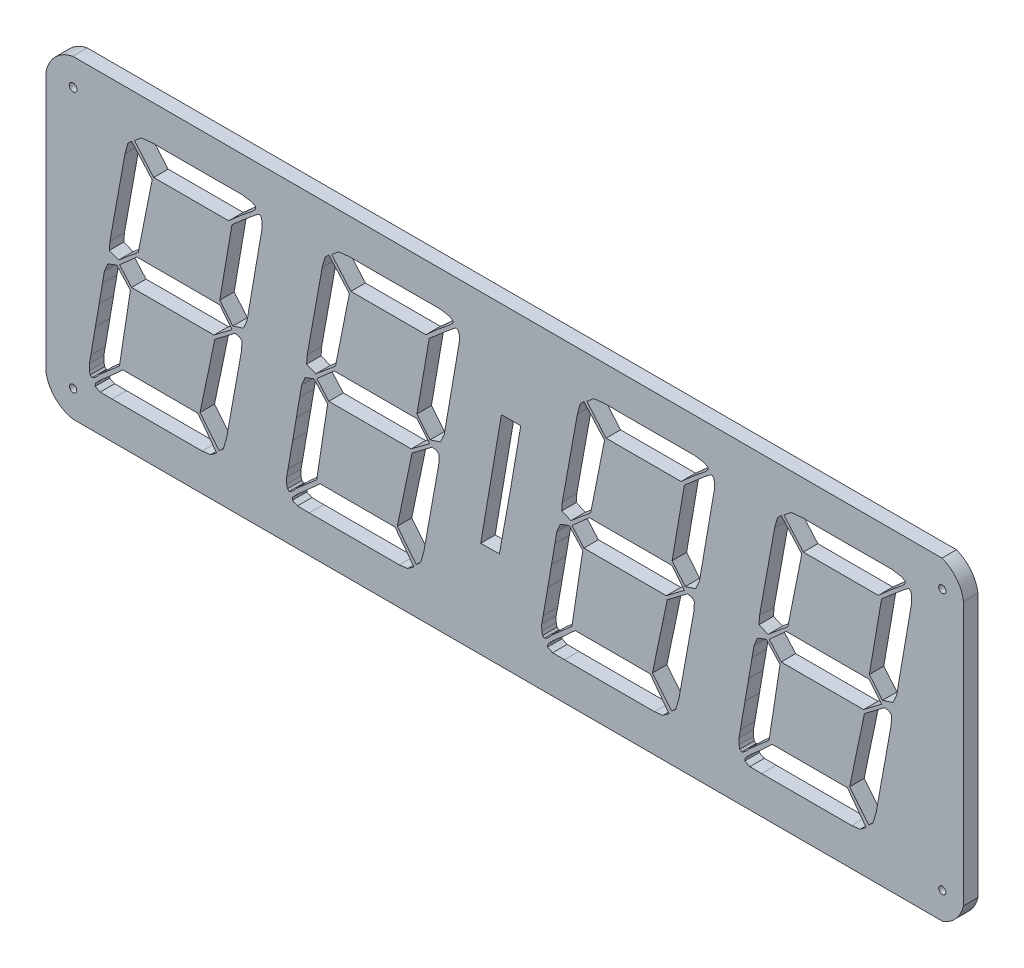
SolidWorks part; units mm, degrees
ref_plane "Alzado" through (0, 0, 0) normal (0, 0, 1) x (1, 0, 0)
ref_plane "Planta" through (0, 0, 0) normal (0, 1, 0) x (1, 0, 0)
ref_plane "Vista lateral" through (0, 0, 0) normal (1, 0, 0) x (0, 0, -1)
sketch "Model" plane through (0, 0, 0) normal (0, 0, 1) x (1, 0, 0)
  line L0 (-140.6225, 55.7522) -> (-140.6299, -52.2478)
  line L1 (-129.5522, 66.8002) -> (230.4478, 66.8126)
  line L2 (239.3651, 55.7522) -> (239.368, -53.5141)
  line L3 (230.8631, -63.3329) -> (-129.5522, -63.3205)
  line L4 (-64.9575, 40.0838) -> (-96.0301, 40.0838)
  line L5 (-96.0301, 40.0838) -> (-103.9988, 49.3198)
  line L6 (-110.1562, 1.7368) -> (-102.93, 8.0807)
  line L7 (-102.93, 8.0807) -> (-68.6104, 8.0807)
  line L8 (-68.6104, 8.0807) -> (-63.6119, 1.7368)
  line L9 (-63.6119, 1.7368) -> (-71.0723, -3.9362)
  line L10 (-71.0723, -3.9362) -> (-105.2054, -3.9362)
  line L11 (-105.2054, -3.9362) -> (-110.1562, 1.7368)
  line L12 (-108.8288, -35.3192) -> (-77.7561, -35.3192)
  line L13 (-77.7561, -35.3192) -> (-69.9507, -45.704)
  line L14 (-55.7324, 46.1598) -> (-63.6119, 39.3989)
  line L15 (-63.6119, 39.3989) -> (-68.6828, 9.7484)
  line L16 (-68.6828, 9.7484) -> (-63.2554, 3.1978)
  line L17 (-105.1896, 48.562) -> (-96.6695, 38.9507)
  line L18 (-96.6695, 38.9507) -> (-102.4115, 10.0574)
  line L19 (-102.4115, 10.0574) -> (-110.5903, 3.1978)
  line L20 (-114.1475, 8.141) -> (-107.9276, 42.67)
  line L21 (-118.6586, -41.9453) -> (-110.2023, -34.6026)
  line L22 (-110.2023, -34.6026) -> (-105.6821, -5.1361)
  line L23 (-105.6821, -5.1361) -> (-111.3311, 1.0276)
  line L24 (-68.9232, -44.3791) -> (-76.8319, -34.6002)
  line L25 (-76.8319, -34.6002) -> (-70.708, -5.2612)
  line L26 (-70.708, -5.2612) -> (-62.3439, 1.0154)
  line L27 (-59.6661, -3.9289) -> (-65.8858, -38.4574)
  line L28 (16.7253, 40.0838) -> (-14.3473, 40.0838)
  line L29 (-14.3473, 40.0838) -> (-22.316, 49.3198)
  line L30 (-28.4733, 1.7368) -> (-21.2471, 8.0807)
  line L31 (-21.2471, 8.0807) -> (13.0724, 8.0807)
  line L32 (13.0724, 8.0807) -> (18.1947, 1.7368)
  line L33 (18.1947, 1.7368) -> (10.6105, -3.9362)
  line L34 (10.6105, -3.9362) -> (-23.5226, -3.9362)
  line L35 (-23.5226, -3.9362) -> (-28.4733, 1.7368)
  line L36 (-27.1459, -35.3192) -> (3.9267, -35.3192)
  line L37 (3.9267, -35.3192) -> (11.7321, -45.704)
  line L38 (25.9504, 46.1916) -> (18.071, 39.4307)
  line L39 (18.071, 39.4307) -> (13, 9.7801)
  line L40 (13, 9.7801) -> (18.4274, 3.2296)
  line L41 (-23.5068, 48.5938) -> (-14.9867, 38.9825)
  line L42 (-14.9867, 38.9825) -> (-20.7287, 10.0892)
  line L43 (-20.7287, 10.0892) -> (-28.9075, 3.2296)
  line L44 (-32.4647, 8.1728) -> (-26.2448, 42.7018)
  line L45 (-36.9758, -41.9135) -> (-28.5195, -34.5709)
  line L46 (-28.5195, -34.5709) -> (-23.9993, -5.1043)
  line L47 (-23.9993, -5.1043) -> (-29.6483, 1.0594)
  line L48 (12.7596, -44.3473) -> (4.8509, -34.5684)
  line L49 (4.8509, -34.5684) -> (10.9749, -5.2294)
  line L50 (10.9749, -5.2294) -> (19.3389, 1.0472)
  line L51 (22.0168, -3.8971) -> (15.797, -38.4256)
  line L52 (122.4056, 40.26) -> (91.3329, 40.26)
  line L53 (91.3329, 40.26) -> (83.3642, 49.496)
  line L54 (77.2069, 1.913) -> (84.3607, 8.2568)
  line L55 (84.3607, 8.2568) -> (118.6802, 8.2568)
  line L56 (118.6802, 8.2568) -> (123.7512, 1.913)
  line L57 (123.7512, 1.913) -> (116.2907, -3.7601)
  line L58 (116.2907, -3.7601) -> (82.1576, -3.7601)
  line L59 (82.1576, -3.7601) -> (77.2069, 1.913)
  line L60 (78.5343, -35.143) -> (109.6069, -35.143)
  line L61 (109.6069, -35.143) -> (117.4122, -45.5279)
  line L62 (131.6306, 46.3995) -> (123.7512, 39.6386)
  line L63 (123.7512, 39.6386) -> (118.6802, 9.9881)
  line L64 (118.6802, 9.9881) -> (124.1076, 3.4375)
  line L65 (82.1734, 48.8017) -> (90.6935, 39.1904)
  line L66 (90.6935, 39.1904) -> (84.9515, 10.2971)
  line L67 (84.9515, 10.2971) -> (76.7727, 3.4375)
  line L68 (73.2155, 8.3807) -> (79.4354, 42.9097)
  line L69 (68.7044, -41.7056) -> (77.1607, -34.3629)
  line L70 (77.1607, -34.3629) -> (81.6809, -4.8964)
  line L71 (81.6809, -4.8964) -> (76.0319, 1.2673)
  line L72 (118.4398, -44.1394) -> (110.5311, -34.3605)
  line L73 (110.5311, -34.3605) -> (116.6551, -5.0215)
  line L74 (116.6551, -5.0215) -> (125.0191, 1.2552)
  line L75 (127.697, -3.6892) -> (121.4772, -38.2177)
  line L76 (204.0884, 40.26) -> (173.0157, 40.26)
  line L77 (173.0157, 40.26) -> (165.047, 49.496)
  line L78 (158.8897, 1.913) -> (165.9593, 8.2568)
  line L79 (165.9593, 8.2568) -> (200.2788, 8.2568)
  line L80 (200.2788, 8.2568) -> (205.434, 1.913)
  line L81 (205.434, 1.913) -> (197.9736, -3.7601)
  line L82 (197.9736, -3.7601) -> (163.8405, -3.7601)
  line L83 (163.8405, -3.7601) -> (158.8897, 1.913)
  line L84 (160.2171, -35.143) -> (191.2898, -35.143)
  line L85 (191.2898, -35.143) -> (199.0951, -45.5279)
  line L86 (213.3134, 46.4313) -> (205.434, 39.6704)
  line L87 (205.434, 39.6704) -> (200.363, 10.0198)
  line L88 (200.363, 10.0198) -> (205.7903, 3.4693)
  line L89 (163.8562, 48.8335) -> (172.3763, 39.2222)
  line L90 (172.3763, 39.2222) -> (166.6343, 10.3289)
  line L91 (166.6343, 10.3289) -> (158.4554, 3.4693)
  line L92 (154.8984, 8.4125) -> (161.1182, 42.9415)
  line L93 (150.3872, -41.6738) -> (158.8435, -34.3311)
  line L94 (158.8435, -34.3311) -> (163.3638, -4.8646)
  line L95 (163.3638, -4.8646) -> (157.7147, 1.2991)
  line L96 (200.1227, -44.1076) -> (192.214, -34.3287)
  line L97 (192.214, -34.3287) -> (198.3379, -4.9897)
  line L98 (198.3379, -4.9897) -> (206.7019, 1.2869)
  line L99 (209.3798, -3.6574) -> (203.1599, -38.1859)
  line L100 (-103.9988, 49.3198) -> (-101.137, 51.7291)
  line L101 (-101.137, 51.7291) -> (-96.392, 52.2351)
  line L102 (-96.392, 52.2351) -> (-90.8081, 52.1862)
  line L103 (-90.8081, 52.1862) -> (-81.4945, 52.1759)
  line L104 (-81.4945, 52.1759) -> (-71.5603, 52.1951)
  line L105 (-71.5603, 52.1951) -> (-59.3236, 52.2382)
  line L106 (-59.3236, 52.2382) -> (-55.3145, 51.5899)
  line L107 (-55.3145, 51.5899) -> (-53.8742, 50.7516)
  line L108 (-53.8742, 50.7516) -> (-53.7847, 49.9239)
  line L109 (-53.7847, 49.9239) -> (-55.0086, 48.562)
  line L110 (-55.0086, 48.562) -> (-60.0916, 44.4166)
  line L111 (-60.0916, 44.4166) -> (-64.9575, 40.0838)
  line L112 (-69.9507, -45.704) -> (-72.4976, -47.5521)
  line L113 (-72.4976, -47.5521) -> (-75.986, -47.9957)
  line L114 (-75.986, -47.9957) -> (-113.2949, -47.9957)
  line L115 (-113.2949, -47.9957) -> (-118.1689, -47.9461)
  line L116 (-118.1689, -47.9461) -> (-120.2715, -46.9653)
  line L117 (-120.2715, -46.9653) -> (-120.1336, -45.794)
  line L118 (-120.1336, -45.794) -> (-118.0338, -43.5885)
  line L119 (-118.0338, -43.5885) -> (-114.0258, -40.0909)
  line L120 (-114.0258, -40.0909) -> (-108.8288, -35.3192)
  line L121 (-52.2008, 48.7284) -> (-52.3111, 48.7191)
  line L122 (-52.3111, 48.7191) -> (-52.434, 48.6747)
  line L123 (-52.434, 48.6747) -> (-52.7329, 48.5137)
  line L124 (-52.7329, 48.5137) -> (-53.5199, 47.9663)
  line L125 (-53.5199, 47.9663) -> (-55.7324, 46.1598)
  line L126 (-63.2554, 3.1978) -> (-58.9197, 4.5919)
  line L127 (-58.9197, 4.5919) -> (-57.3622, 8.0171)
  line L128 (-57.3622, 8.0171) -> (-56.5792, 12.6326)
  line L129 (-56.5792, 12.6326) -> (-55.1781, 20.8191)
  line L130 (-55.1781, 20.8191) -> (-53.6437, 29.7566)
  line L131 (-53.6437, 29.7566) -> (-51.7277, 40.8987)
  line L132 (-51.7277, 40.8987) -> (-51.1301, 44.252)
  line L133 (-51.1301, 44.252) -> (-51.1454, 46.7087)
  line L134 (-51.1454, 46.7087) -> (-51.4988, 48.1027)
  line L135 (-51.4988, 48.1027) -> (-52.2008, 48.7284)
  line L136 (-107.9276, 42.67) -> (-106.7219, 47.0167)
  line L137 (-106.7219, 47.0167) -> (-105.1896, 48.562)
  line L138 (-110.5903, 3.1978) -> (-114.3946, 4.748)
  line L139 (-114.3946, 4.748) -> (-114.1475, 8.141)
  line L140 (-111.3311, 1.0276) -> (-115.0422, -0.3762)
  line L141 (-115.0422, -0.3762) -> (-116.4501, -3.8038)
  line L142 (-116.4501, -3.8038) -> (-117.233, -8.4194)
  line L143 (-117.233, -8.4194) -> (-118.6337, -16.6062)
  line L144 (-118.6337, -16.6062) -> (-120.1676, -25.5441)
  line L145 (-120.1676, -25.5441) -> (-122.0828, -36.6867)
  line L146 (-122.0828, -36.6867) -> (-122.6824, -40.0386)
  line L147 (-122.6824, -40.0386) -> (-122.6675, -42.4954)
  line L148 (-122.6675, -42.4954) -> (-122.3132, -43.8899)
  line L149 (-122.3132, -43.8899) -> (-121.6116, -44.5151)
  line L150 (-65.8858, -38.4574) -> (-67.1852, -42.8137)
  line L151 (-67.1852, -42.8137) -> (-68.9232, -44.3791)
  line L152 (-62.3439, 1.0154) -> (-60.5122, 0.7064)
  line L153 (-60.5122, 0.7064) -> (-59.4554, -0.2206)
  line L154 (-59.4554, -0.2206) -> (-59.6661, -3.9289)
  line L155 (-22.316, 49.3198) -> (-19.4541, 51.7291)
  line L156 (-19.4541, 51.7291) -> (-14.7092, 52.2351)
  line L157 (-14.7092, 52.2351) -> (-9.1253, 52.1862)
  line L158 (-9.1253, 52.1862) -> (0.1883, 52.1759)
  line L159 (0.1883, 52.1759) -> (10.1225, 52.1951)
  line L160 (10.1225, 52.1951) -> (22.3592, 52.2382)
  line L161 (22.3592, 52.2382) -> (26.3683, 51.5899)
  line L162 (26.3683, 51.5899) -> (27.8086, 50.7516)
  line L163 (27.8086, 50.7516) -> (27.8981, 49.9239)
  line L164 (27.8981, 49.9239) -> (26.6742, 48.562)
  line L165 (26.6742, 48.562) -> (21.5912, 44.4166)
  line L166 (21.5912, 44.4166) -> (16.7253, 40.0838)
  line L167 (11.7321, -45.704) -> (9.1853, -47.5521)
  line L168 (9.1853, -47.5521) -> (5.6968, -47.9957)
  line L169 (5.6968, -47.9957) -> (-31.6121, -47.9957)
  line L170 (-31.6121, -47.9957) -> (-36.486, -47.9461)
  line L171 (-36.486, -47.9461) -> (-38.5886, -46.9653)
  line L172 (-38.5886, -46.9653) -> (-38.4508, -45.794)
  line L173 (-38.4508, -45.794) -> (-36.3509, -43.5885)
  line L174 (-36.3509, -43.5885) -> (-32.343, -40.0909)
  line L175 (-32.343, -40.0909) -> (-27.1459, -35.3192)
  line L176 (29.4821, 48.7602) -> (29.3718, 48.7509)
  line L177 (29.3718, 48.7509) -> (29.2488, 48.7064)
  line L178 (29.2488, 48.7064) -> (28.9499, 48.5455)
  line L179 (28.9499, 48.5455) -> (28.163, 47.998)
  line L180 (28.163, 47.998) -> (25.9504, 46.1916)
  line L181 (18.4274, 3.2296) -> (22.7631, 4.6237)
  line L182 (22.7631, 4.6237) -> (24.3206, 8.0489)
  line L183 (24.3206, 8.0489) -> (25.1036, 12.6644)
  line L184 (25.1036, 12.6644) -> (26.5047, 20.8509)
  line L185 (26.5047, 20.8509) -> (28.0391, 29.7884)
  line L186 (28.0391, 29.7884) -> (29.9551, 40.9305)
  line L187 (29.9551, 40.9305) -> (30.5528, 44.2838)
  line L188 (30.5528, 44.2838) -> (30.5374, 46.7405)
  line L189 (30.5374, 46.7405) -> (30.184, 48.1344)
  line L190 (30.184, 48.1344) -> (29.4821, 48.7602)
  line L191 (-26.2448, 42.7018) -> (-25.039, 47.0485)
  line L192 (-25.039, 47.0485) -> (-23.5068, 48.5938)
  line L193 (-28.9075, 3.2296) -> (-32.7117, 4.7798)
  line L194 (-32.7117, 4.7798) -> (-32.4647, 8.1728)
  line L195 (-29.6483, 1.0594) -> (-33.3594, -0.3444)
  line L196 (-33.3594, -0.3444) -> (-34.7673, -3.7721)
  line L197 (-34.7673, -3.7721) -> (-35.5502, -8.3876)
  line L198 (-35.5502, -8.3876) -> (-36.9508, -16.5744)
  line L199 (-36.9508, -16.5744) -> (-38.4847, -25.5123)
  line L200 (-38.4847, -25.5123) -> (-40.4, -36.6549)
  line L201 (-40.4, -36.6549) -> (-40.9996, -40.0068)
  line L202 (-40.9996, -40.0068) -> (-40.9847, -42.4636)
  line L203 (-40.9847, -42.4636) -> (-40.6304, -43.8581)
  line L204 (-40.6304, -43.8581) -> (-39.9288, -44.4833)
  line L205 (15.797, -38.4256) -> (14.4977, -42.7819)
  line L206 (14.4977, -42.7819) -> (12.7596, -44.3473)
  line L207 (19.3389, 1.0472) -> (21.1706, 0.7382)
  line L208 (21.1706, 0.7382) -> (22.2275, -0.1889)
  line L209 (22.2275, -0.1889) -> (22.0168, -3.8971)
  line L210 (83.3642, 49.496) -> (86.2261, 51.9052)
  line L211 (86.2261, 51.9052) -> (90.971, 52.4113)
  line L212 (90.971, 52.4113) -> (96.5549, 52.3623)
  line L213 (96.5549, 52.3623) -> (105.8685, 52.3521)
  line L214 (105.8685, 52.3521) -> (115.8027, 52.3712)
  line L215 (115.8027, 52.3712) -> (128.0394, 52.4143)
  line L216 (128.0394, 52.4143) -> (132.0485, 51.766)
  line L217 (132.0485, 51.766) -> (133.4888, 50.9278)
  line L218 (133.4888, 50.9278) -> (133.5783, 50.1001)
  line L219 (133.5783, 50.1001) -> (132.3544, 48.7381)
  line L220 (132.3544, 48.7381) -> (127.2714, 44.5927)
  line L221 (127.2714, 44.5927) -> (122.4056, 40.26)
  line L222 (117.4122, -45.5279) -> (114.8655, -47.3759)
  line L223 (114.8655, -47.3759) -> (111.377, -47.8196)
  line L224 (111.377, -47.8196) -> (74.0681, -47.8196)
  line L225 (74.0681, -47.8196) -> (69.1942, -47.77)
  line L226 (69.1942, -47.77) -> (67.0916, -46.7891)
  line L227 (67.0916, -46.7891) -> (67.2294, -45.6179)
  line L228 (67.2294, -45.6179) -> (69.3292, -43.4123)
  line L229 (69.3292, -43.4123) -> (73.3372, -39.9148)
  line L230 (73.3372, -39.9148) -> (78.5343, -35.143)
  line L231 (135.1623, 48.9681) -> (135.052, 48.9589)
  line L232 (135.052, 48.9589) -> (134.929, 48.9144)
  line L233 (134.929, 48.9144) -> (134.6301, 48.7534)
  line L234 (134.6301, 48.7534) -> (133.8432, 48.206)
  line L235 (133.8432, 48.206) -> (131.6306, 46.3995)
  line L236 (124.1076, 3.4375) -> (128.4433, 4.8316)
  line L237 (128.4433, 4.8316) -> (130.0008, 8.2568)
  line L238 (130.0008, 8.2568) -> (130.7839, 12.8723)
  line L239 (130.7839, 12.8723) -> (132.1849, 21.0588)
  line L240 (132.1849, 21.0588) -> (133.7193, 29.9963)
  line L241 (133.7193, 29.9963) -> (135.6353, 41.1384)
  line L242 (135.6353, 41.1384) -> (136.233, 44.4917)
  line L243 (136.233, 44.4917) -> (136.2176, 46.9484)
  line L244 (136.2176, 46.9484) -> (135.8642, 48.3424)
  line L245 (135.8642, 48.3424) -> (135.1623, 48.9681)
  line L246 (79.4354, 42.9097) -> (80.6412, 47.2564)
  line L247 (80.6412, 47.2564) -> (82.1734, 48.8017)
  line L248 (76.7727, 3.4375) -> (72.9685, 4.9877)
  line L249 (72.9685, 4.9877) -> (73.2155, 8.3807)
  line L250 (76.0319, 1.2673) -> (72.3208, -0.1365)
  line L251 (72.3208, -0.1365) -> (70.9129, -3.5641)
  line L252 (70.9129, -3.5641) -> (70.13, -8.1797)
  line L253 (70.13, -8.1797) -> (68.7294, -16.3665)
  line L254 (68.7294, -16.3665) -> (67.1955, -25.3044)
  line L255 (67.1955, -25.3044) -> (65.2802, -36.447)
  line L256 (65.2802, -36.447) -> (64.6806, -39.7989)
  line L257 (64.6806, -39.7989) -> (64.6954, -42.2557)
  line L258 (64.6954, -42.2557) -> (65.0498, -43.6502)
  line L259 (65.0498, -43.6502) -> (65.7514, -44.2754)
  line L260 (121.4772, -38.2177) -> (120.1779, -42.574)
  line L261 (120.1779, -42.574) -> (118.4398, -44.1394)
  line L262 (125.0191, 1.2552) -> (126.8508, 0.9461)
  line L263 (126.8508, 0.9461) -> (127.9077, 0.0191)
  line L264 (127.9077, 0.0191) -> (127.697, -3.6892)
  line L265 (165.047, 49.496) -> (167.9089, 51.9052)
  line L266 (167.9089, 51.9052) -> (172.6538, 52.4113)
  line L267 (172.6538, 52.4113) -> (178.2378, 52.3623)
  line L268 (178.2378, 52.3623) -> (187.5513, 52.3521)
  line L269 (187.5513, 52.3521) -> (197.4856, 52.3712)
  line L270 (197.4856, 52.3712) -> (209.7222, 52.4143)
  line L271 (209.7222, 52.4143) -> (213.7314, 51.766)
  line L272 (213.7314, 51.766) -> (215.1716, 50.9278)
  line L273 (215.1716, 50.9278) -> (215.2611, 50.1001)
  line L274 (215.2611, 50.1001) -> (214.0372, 48.7381)
  line L275 (214.0372, 48.7381) -> (208.9543, 44.5927)
  line L276 (208.9543, 44.5927) -> (204.0884, 40.26)
  line L277 (199.0951, -45.5279) -> (196.5483, -47.3759)
  line L278 (196.5483, -47.3759) -> (193.0598, -47.8196)
  line L279 (193.0598, -47.8196) -> (155.7509, -47.8196)
  line L280 (155.7509, -47.8196) -> (150.877, -47.77)
  line L281 (150.877, -47.77) -> (148.7744, -46.7891)
  line L282 (148.7744, -46.7891) -> (148.9123, -45.6179)
  line L283 (148.9123, -45.6179) -> (151.012, -43.4123)
  line L284 (151.012, -43.4123) -> (155.02, -39.9148)
  line L285 (155.02, -39.9148) -> (160.2171, -35.143)
  line L286 (216.8451, 48.9999) -> (216.7348, 48.9906)
  line L287 (216.7348, 48.9906) -> (216.6119, 48.9461)
  line L288 (216.6119, 48.9461) -> (216.313, 48.7852)
  line L289 (216.313, 48.7852) -> (215.526, 48.2377)
  line L290 (215.526, 48.2377) -> (213.3134, 46.4313)
  line L291 (205.7903, 3.4693) -> (210.1262, 4.8634)
  line L292 (210.1262, 4.8634) -> (211.6836, 8.2886)
  line L293 (211.6836, 8.2886) -> (212.4667, 12.9041)
  line L294 (212.4667, 12.9041) -> (213.8678, 21.0906)
  line L295 (213.8678, 21.0906) -> (215.4022, 30.0281)
  line L296 (215.4022, 30.0281) -> (217.3181, 41.1702)
  line L297 (217.3181, 41.1702) -> (217.9158, 44.5235)
  line L298 (217.9158, 44.5235) -> (217.9004, 46.9802)
  line L299 (217.9004, 46.9802) -> (217.5471, 48.3741)
  line L300 (217.5471, 48.3741) -> (216.8451, 48.9999)
  line L301 (161.1182, 42.9415) -> (162.324, 47.2882)
  line L302 (162.324, 47.2882) -> (163.8562, 48.8335)
  line L303 (158.4554, 3.4693) -> (154.6513, 5.0195)
  line L304 (154.6513, 5.0195) -> (154.8984, 8.4125)
  line L305 (157.7147, 1.2991) -> (154.0036, -0.1047)
  line L306 (154.0036, -0.1047) -> (152.5957, -3.5324)
  line L307 (152.5957, -3.5324) -> (151.8128, -8.1479)
  line L308 (151.8128, -8.1479) -> (150.4122, -16.3347)
  line L309 (150.4122, -16.3347) -> (148.8783, -25.2726)
  line L310 (148.8783, -25.2726) -> (146.963, -36.4152)
  line L311 (146.963, -36.4152) -> (146.3634, -39.7671)
  line L312 (146.3634, -39.7671) -> (146.3783, -42.2239)
  line L313 (146.3783, -42.2239) -> (146.7326, -43.6184)
  line L314 (146.7326, -43.6184) -> (147.4343, -44.2436)
  line L315 (203.1599, -38.1859) -> (201.8607, -42.5422)
  line L316 (201.8607, -42.5422) -> (200.1227, -44.1076)
  line L317 (206.7019, 1.2869) -> (208.5336, 0.9779)
  line L318 (208.5336, 0.9779) -> (209.5905, 0.0508)
  line L319 (209.5905, 0.0508) -> (209.3798, -3.6574)
  line L320 (-129.4104, 66.7349) -> (-129.4104, -63.2651) construction
  line L322 (79.4354, 42.9097) -> (73.2155, 8.3807) construction
  line L323 (123.7512, 39.6386) -> (-14.9867, 38.9825) construction
  line L324 (77.2069, 1.913) -> (18.1947, 1.7368) construction
  line L325 (47.142, -23.3314) -> (39.4096, -23.4039)
  line L326 (110.5311, -34.3605) -> (-28.5195, -34.5709) construction
  line L327 (55.992, 27.0537) -> (47.9831, 27.0298)
  line L328 (230.5896, 66.7349) -> (230.5896, -63.2651) construction
  line L329 (51.7053, 1.8369) -> (55.992, 27.0537)
  line L330 (51.7053, 1.8369) -> (47.142, -23.3314)
  line L331 (43.6963, 1.813) -> (47.9831, 27.0298)
  line L332 (43.6963, 1.813) -> (39.4096, -23.4039)
  line L333 (-140.628, -52.2632) -> (239.372, -52.2632) construction
  arc A0 (-129.5522, 66.8002) -> (-140.6225, 55.7522) centre (-126.8845, 53.0567) ccw
  arc A1 (239.3651, 55.7522) -> (230.4478, 66.8126) centre (225.5147, 53.7105) ccw
  arc A2 (-140.6299, -52.2478) -> (-129.5522, -63.3205) centre (-126.8871, -49.5765) ccw
  arc A3 (230.8631, -63.3329) -> (239.368, -53.5141) centre (225.7411, -50.3035) ccw
  circle A4 centre (-129.4104, 55.7368) radius 1.6
  circle A5 centre (-129.4104, -52.2632) radius 1.5017
  circle A6 centre (230.5896, -52.2632) radius 1.5017
  circle A7 centre (230.5896, 55.7368) radius 1.5017
  arc A8 (-121.6116, -44.5151) -> (-118.6586, -41.9453) centre (-124.3353, -38.4037) ccw
  arc A9 (-39.9288, -44.4833) -> (-36.9758, -41.9135) centre (-42.6521, -38.3724) ccw
  arc A10 (65.7514, -44.2754) -> (68.7044, -41.7056) centre (63.0283, -38.1647) ccw
  arc A11 (147.4343, -44.2436) -> (150.3872, -41.6738) centre (144.711, -38.1328) ccw
  point P344 (-140.628, 1.7368)
  point P345 (35.6295, 66.8096)
  point P346 (0, 0)
  point P348 (0, 0)
  point P349 (225.896, -50.2437)
  point P350 (0, 0)
  point P356 (226.9053, -49.5805)
  point P357 (225.5147, -50.4409)
  dimension "D1" = 108
  dimension "D5" = 14
  dimension "D6" = 14
  dimension "D7" = 14
  dimension "D8" = 14
  dimension "D2" = 360
  dimension "D3" = 380
  dimension "D4" = 130.1455
extrude "Saliente-Extruir1" add sketch "Model" along normal blind 6
